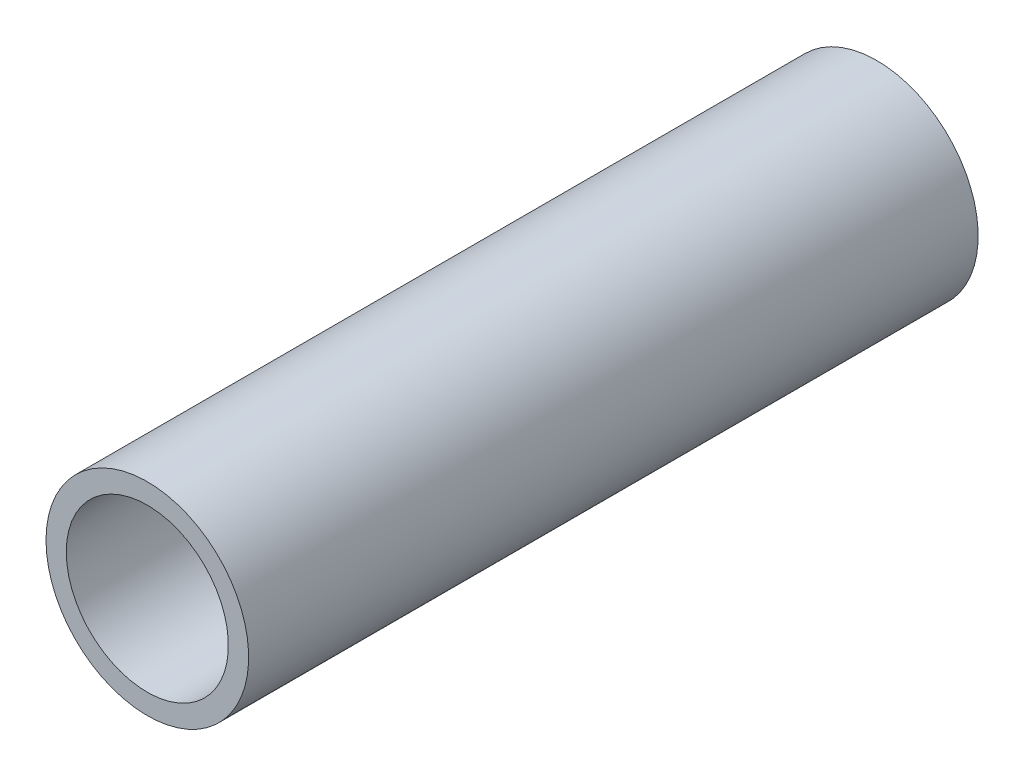
SolidWorks part; units mm, degrees
ref_plane "Plano frontal" through (0, 0, 0) normal (0, 0, 1) x (1, 0, 0)
ref_plane "Plano superior" through (0, 0, 0) normal (0, 1, 0) x (1, 0, 0)
ref_plane "Plano direito" through (0, 0, 0) normal (1, 0, 0) x (0, 0, -1)
sketch "Esboço1" plane through (0, 0, 0) normal (0, 0, 1) x (1, 0, 0)
  circle A0 centre (0, 0) radius 12.5
  circle A1 centre (0, 0) radius 10
  dimension "D1" = 25
  dimension "D2" = 20
extrude "Ressalto-extrusão1" add sketch "Esboço1" along normal blind 90
